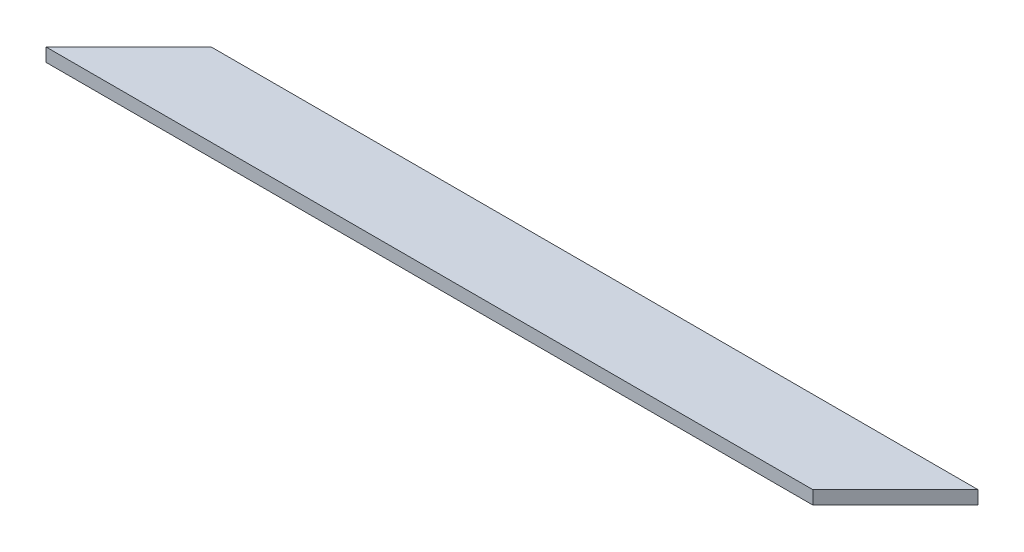
SolidWorks part; units mm, degrees
material "PE High Density"
ref_plane "Front Plane" through (0, 0, 0) normal (0, 0, 1) x (1, 0, 0)
ref_plane "Top Plane" through (0, 0, 0) normal (0, 1, 0) x (1, 0, 0)
ref_plane "Right Plane" through (0, 0, 0) normal (1, 0, 0) x (0, 0, -1)
sketch "Sketch2" plane through (0, 0, 0) normal (0, 1, 0) x (1, 0, 0)
  line L0 (-6617.4938, 2309.8125) -> (-6617.4938, 2176.4625) construction
  line L1 (-6617.4938, 2309.8125) -> (-5379.2438, 2309.8125)
  line L3 (-6750.8438, 2176.4625) -> (-5512.5938, 2176.4625)
  line L5 (-5379.2438, 2309.8125) -> (-5512.5938, 2309.8125) construction
  line L6 (-6750.8438, 2176.4625) -> (-6617.4938, 2309.8125)
  line L7 (-5512.5938, 2309.8125) -> (-5512.5938, 2176.4625) construction
  line L8 (-5379.2438, 2309.8125) -> (-5512.5938, 2176.4625)
  dimension "D1" = 133.35
  dimension "D2" = 1371.6
  dimension "D3" = 133.35
  dimension "D4" = 133.35
  dimension "D5" = 1104.9
extrude "Boss-Extrude1" add sketch "Sketch2" along normal blind 21.59 contours L3 L8 L1 L6
